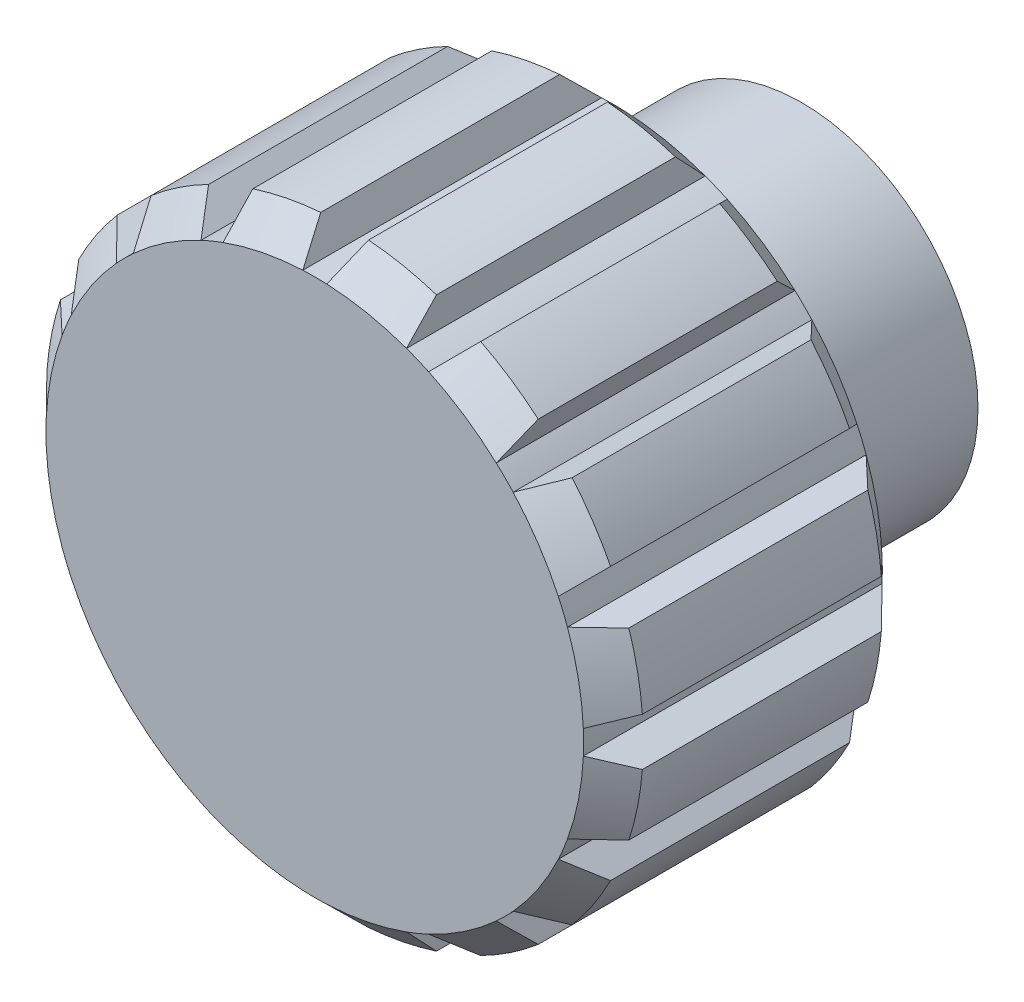
SolidWorks part; units mm, degrees
ref_plane "Front Plane" through (0, 0, 0) normal (0, 0, 1) x (1, 0, 0)
ref_plane "Top Plane" through (0, 0, 0) normal (0, 1, 0) x (1, 0, 0)
ref_plane "Right Plane" through (0, 0, 0) normal (1, 0, 0) x (0, 0, -1)
sketch "Sketch1" plane through (0, 0, 0) normal (0, 0, 1) x (1, 0, 0)
  line L0 (-4.8913, 1.651) -> (5.2009, 1.651)
  line L1 (0, -3.175) -> (0, 5.3092) construction
  circle A0 centre (0, 0) radius 3.175
  circle A1 centre (0, 0) radius 7.5
  dimension "D1" = 6.35
  dimension "D2" = 15
  dimension "D3" = 4.826
extrude "Boss-Extrude1" add sketch "Sketch1" along normal blind 8
sketch "Sketch2" plane through (0, 0, 8) normal (0, 0, 1) x (1, 0, 0)
  circle A0 centre (0, 0) radius 12.7
  dimension "D1" = 25.4
extrude "Boss-Extrude2" add sketch "Sketch2" along normal blind 12.7
chamfer "Chamfer1" distance 1.27 angle 45 2 edges at (12.7, 0, 20.7) (12.7, 0, 8)
sketch "Sketch3" plane through (0, 0, 20.7) normal (0, 0, 1) x (1, 0, 0)
  line L0 (0, 13.8231) -> (0, 0) construction
  line L1 (-1.4946, 13.8231) -> (-0.508, 11.4187)
  line L2 (1.4946, 13.8231) -> (0.508, 11.4187)
  line L3 (-1.8993, 13.8231) -> (1.9378, 13.8231) construction
  line L4 (-1.4946, 13.8231) -> (1.4946, 13.8231)
  line L5 (3.9091, 13.3428) -> (6.6707, 12.1989)
  line L6 (6.6707, 12.1989) -> (4.8391, 10.3551)
  line L7 (3.9091, 13.3428) -> (3.9004, 10.7439)
  line L8 (8.7176, 10.8312) -> (10.8312, 8.7176)
  line L9 (10.8312, 8.7176) -> (8.4335, 7.715)
  line L10 (8.7176, 10.8312) -> (7.715, 8.4335)
  line L11 (12.1989, 6.6707) -> (13.3428, 3.9091)
  line L12 (13.3428, 3.9091) -> (10.7439, 3.9004)
  line L13 (12.1989, 6.6707) -> (10.3551, 4.8391)
  line L14 (13.8231, 1.4946) -> (13.8231, -1.4946)
  line L15 (13.8231, -1.4946) -> (11.4187, -0.508)
  line L16 (13.8231, 1.4946) -> (11.4187, 0.508)
  line L17 (13.3428, -3.9091) -> (12.1989, -6.6707)
  line L18 (12.1989, -6.6707) -> (10.3551, -4.8391)
  line L19 (13.3428, -3.9091) -> (10.7439, -3.9004)
  line L20 (10.8312, -8.7176) -> (8.7176, -10.8312)
  line L21 (8.7176, -10.8312) -> (7.715, -8.4335)
  line L22 (10.8312, -8.7176) -> (8.4335, -7.715)
  line L23 (6.6707, -12.1989) -> (3.9091, -13.3428)
  line L24 (3.9091, -13.3428) -> (3.9004, -10.7439)
  line L25 (6.6707, -12.1989) -> (4.8391, -10.3551)
  line L26 (1.4946, -13.8231) -> (-1.4946, -13.8231)
  line L27 (-1.4946, -13.8231) -> (-0.508, -11.4187)
  line L28 (1.4946, -13.8231) -> (0.508, -11.4187)
  line L29 (-3.9091, -13.3428) -> (-6.6707, -12.1989)
  line L30 (-6.6707, -12.1989) -> (-4.8391, -10.3551)
  line L31 (-3.9091, -13.3428) -> (-3.9004, -10.7439)
  line L32 (-8.7176, -10.8312) -> (-10.8312, -8.7176)
  line L33 (-10.8312, -8.7176) -> (-8.4335, -7.715)
  line L34 (-8.7176, -10.8312) -> (-7.715, -8.4335)
  line L35 (-12.1989, -6.6707) -> (-13.3428, -3.9091)
  line L36 (-13.3428, -3.9091) -> (-10.7439, -3.9004)
  line L37 (-12.1989, -6.6707) -> (-10.3551, -4.8391)
  line L38 (-13.8231, -1.4946) -> (-13.8231, 1.4946)
  line L39 (-13.8231, 1.4946) -> (-11.4187, 0.508)
  line L40 (-13.8231, -1.4946) -> (-11.4187, -0.508)
  line L41 (-13.3428, 3.9091) -> (-12.1989, 6.6707)
  line L42 (-12.1989, 6.6707) -> (-10.3551, 4.8391)
  line L43 (-13.3428, 3.9091) -> (-10.7439, 3.9004)
  line L44 (-10.8312, 8.7176) -> (-8.7176, 10.8312)
  line L45 (-8.7176, 10.8312) -> (-7.715, 8.4335)
  line L46 (-10.8312, 8.7176) -> (-8.4335, 7.715)
  line L47 (-6.6707, 12.1989) -> (-3.9091, 13.3428)
  line L48 (-3.9091, 13.3428) -> (-3.9004, 10.7439)
  line L49 (-6.6707, 12.1989) -> (-4.8391, 10.3551)
  circle A1 centre (0, 0) radius 11.43 construction
  arc A2 (0.508, 11.4187) -> (-0.508, 11.4187) centre (0, 0) ccw
  arc A3 (4.8391, 10.3551) -> (3.9004, 10.7439) centre (0, 0) ccw
  arc A4 (8.4335, 7.715) -> (7.715, 8.4335) centre (0, 0) ccw
  arc A5 (10.7439, 3.9004) -> (10.3551, 4.8391) centre (0, 0) ccw
  arc A6 (11.4187, -0.508) -> (11.4187, 0.508) centre (0, 0) ccw
  arc A7 (10.3551, -4.8391) -> (10.7439, -3.9004) centre (0, 0) ccw
  arc A8 (7.715, -8.4335) -> (8.4335, -7.715) centre (0, 0) ccw
  arc A9 (3.9004, -10.7439) -> (4.8391, -10.3551) centre (0, 0) ccw
  arc A10 (-0.508, -11.4187) -> (0.508, -11.4187) centre (0, 0) ccw
  arc A11 (-4.8391, -10.3551) -> (-3.9004, -10.7439) centre (0, 0) ccw
  arc A12 (-8.4335, -7.715) -> (-7.715, -8.4335) centre (0, 0) ccw
  arc A13 (-10.7439, -3.9004) -> (-10.3551, -4.8391) centre (0, 0) ccw
  arc A14 (-11.4187, 0.508) -> (-11.4187, -0.508) centre (0, 0) ccw
  arc A15 (-10.3551, 4.8391) -> (-10.7439, 3.9004) centre (0, 0) ccw
  arc A16 (-7.715, 8.4335) -> (-8.4335, 7.715) centre (0, 0) ccw
  arc A17 (-3.9004, 10.7439) -> (-4.8391, 10.3551) centre (0, 0) ccw
  point P72 (0, 0)
  dimension "D1" = 16
  dimension "D2" = 0.508
extrude "Cut-Extrude2" cut sketch "Sketch3" against normal blind 12.7
